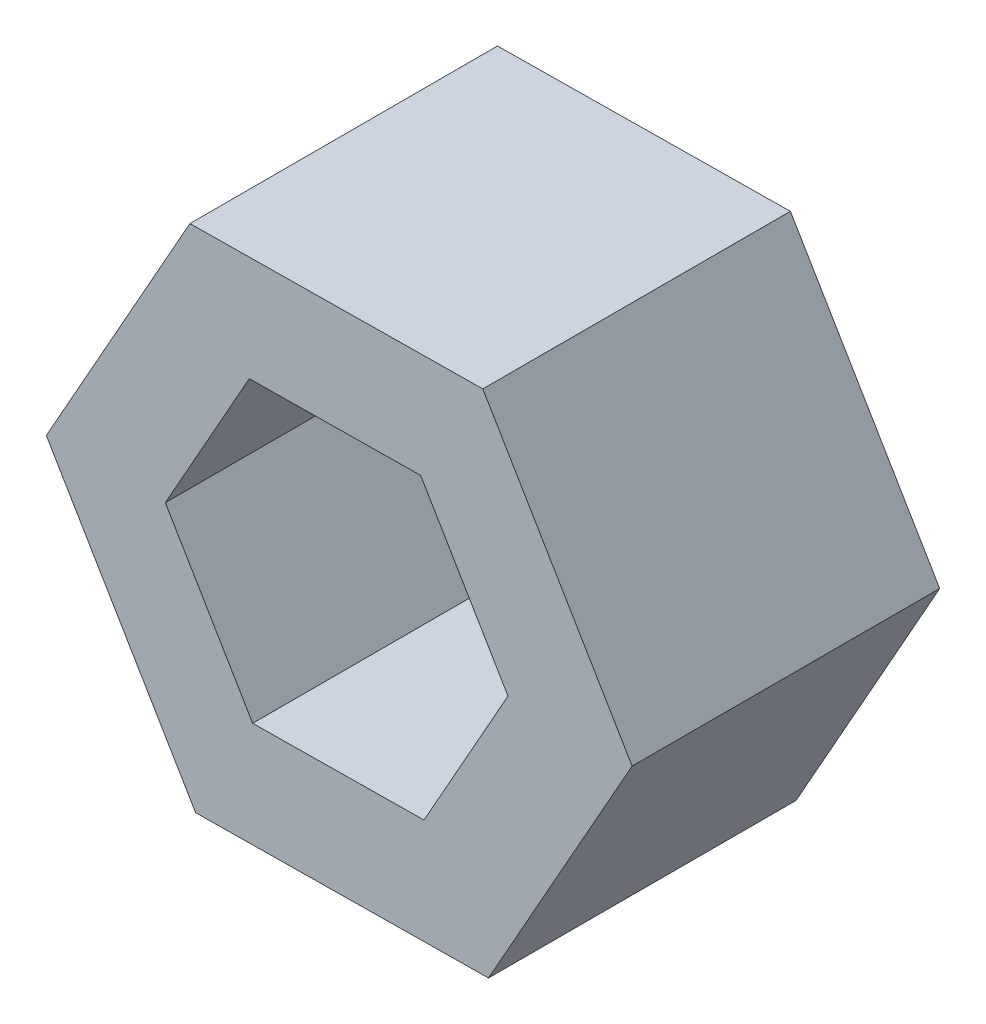
SolidWorks part; units mm, degrees
ref_plane "Front Plane" through (0, 0, 0) normal (0, 0, 1) x (1, 0, 0)
ref_plane "Top Plane" through (0, 0, 0) normal (0, 1, 0) x (1, 0, 0)
ref_plane "Right Plane" through (0, 0, 0) normal (1, 0, 0) x (0, 0, -1)
sketch "Sketch2" plane through (0, 0, 0) normal (0, 0, 1) x (1, 0, 0)
  line L1 (-8.5545, -3.5853) -> (-3.936, -3.5336)
  line L2 (-3.936, -3.5336) -> (-1.6715, 0.4921)
  line L3 (-1.6715, 0.4921) -> (-4.0256, 4.4659)
  line L4 (-4.0256, 4.4659) -> (-8.6441, 4.4142)
  line L5 (-8.6441, 4.4142) -> (-10.9086, 0.3885)
  line L6 (-10.9086, 0.3885) -> (-8.5545, -3.5853)
  circle A0 centre (-6.2901, 0.4403) radius 4 construction
  dimension "D1" = 8
extrude "Boss-Extrude1" add sketch "Sketch2" along normal blind 4.85
sketch "Sketch3" plane through (0, 0, 4.85) normal (0, 0, 1) x (1, 0, 0)
  line L1 (-4.953, -1.8849) -> (-3.6283, 0.4701)
  line L2 (-3.6283, 0.4701) -> (-5.0054, 2.7949)
  line L3 (-5.0054, 2.7949) -> (-7.7073, 2.7646)
  line L4 (-7.7073, 2.7646) -> (-9.032, 0.4096)
  line L5 (-9.032, 0.4096) -> (-7.6548, -1.9151)
  line L6 (-7.6548, -1.9151) -> (-4.953, -1.8849)
  line L7 (-8.5545, -3.5853) -> (-3.936, -3.5336) construction
  circle A0 centre (-6.3301, 0.4399) radius 2.34 construction
  dimension "D1" = 4.68
  dimension "D2" = 1.66
extrude "Cut-Extrude1" cut sketch "Sketch3" against normal through all
